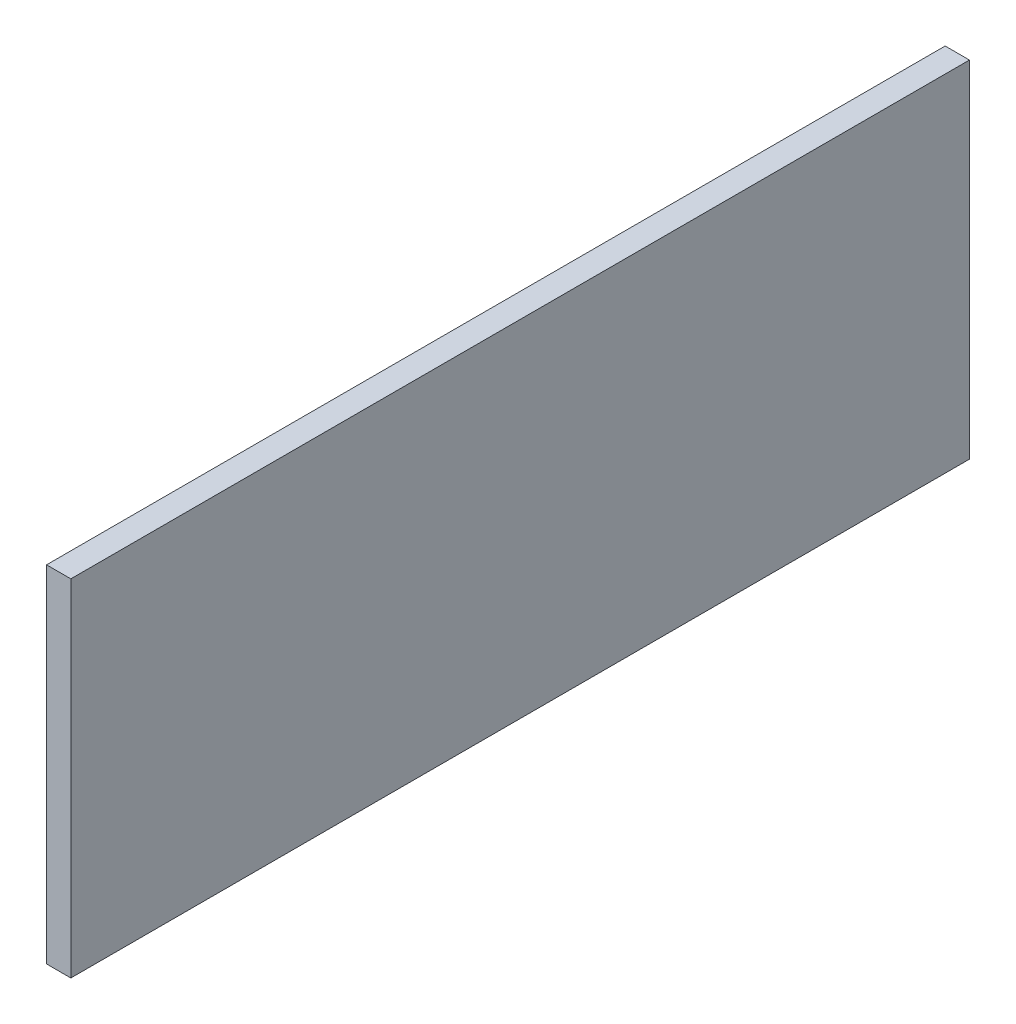
SolidWorks part; units mm, degrees
ref_plane "Front Plane" through (0, 0, 0) normal (0, 0, 1) x (1, 0, 0)
ref_plane "Top Plane" through (0, 0, 0) normal (0, 1, 0) x (1, 0, 0)
ref_plane "Right Plane" through (0, 0, 0) normal (1, 0, 0) x (0, 0, -1)
sketch "Sketch1" plane through (0, 0, 0) normal (1, 0, 0) x (0, 0, -1)
  line L1 (0, 0) -> (222, 0)
  line L2 (0, 0) -> (0, 85.4)
  line L3 (0, 85.4) -> (222, 85.4)
  line L4 (222, 0) -> (222, 85.4)
  dimension "D1" = 85.4
  dimension "D2" = 222
extrude "Boss-Extrude1" add sketch "Sketch1" along normal blind 6
